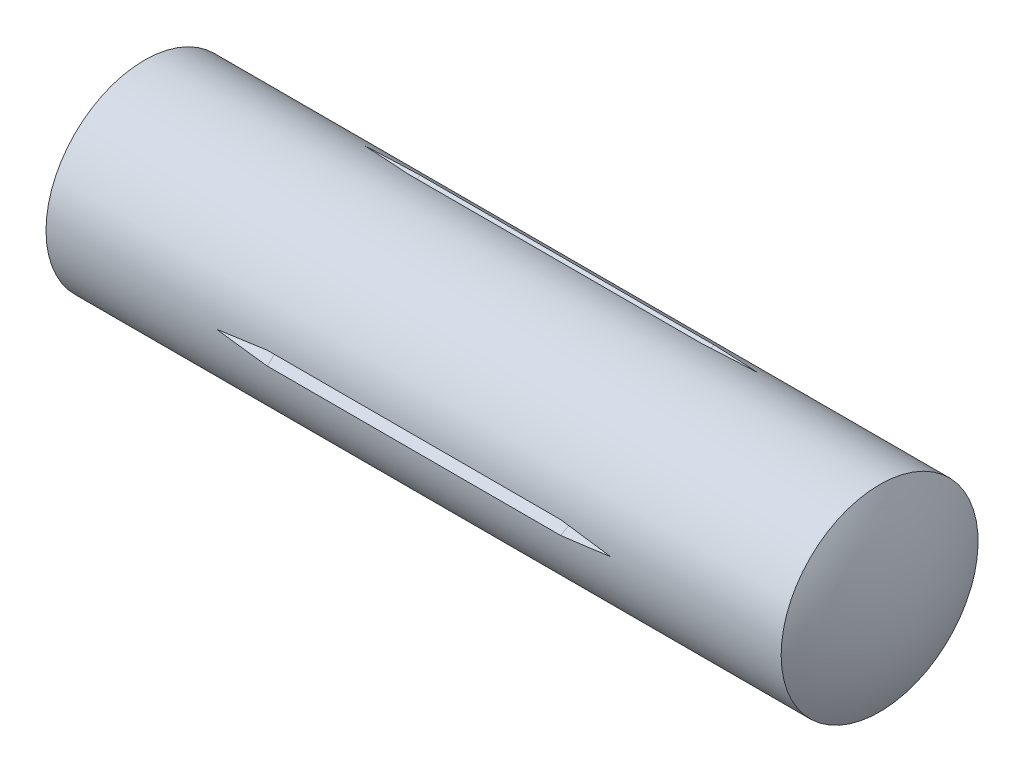
SolidWorks part; units mm, degrees
ref_plane "Plane1" through (0, 0, 0) normal (0, 0, 1) x (1, 0, 0)
ref_plane "Plane2" through (0, 0, 0) normal (0, 1, 0) x (1, 0, 0)
ref_plane "Plane3" through (0, 0, 0) normal (1, 0, 0) x (0, 0, -1)
sketch "Sketch1" plane through (0, 0, 0) normal (0, 0, 1) x (1, 0, 0)
  line L0 (-57, 0) -> (60, 0) construction
  line L1 (-50, 0) -> (-50, 1.25)
  line L2 (-46.6819, 12.5) -> (46.6506, 12.5)
  line L3 (-50, 0) -> (50, 0)
  arc A0 (-46.6819, 12.5) -> (-50, 1.25) centre (-25.0313, 0) ccw
  arc A1 (50, 0) -> (46.6506, 12.5) centre (25, 0) ccw
  dimension "D1" = 25
  dimension "D2" = 25
  dimension "Diameter" = 25
  dimension "Length" = 100
  dimension "D3" = 2.5
revolve "Base-Revolve" add sketch "Sketch1" angle 360 about L0
sketch "Sketch3" plane through (0, 0, 0) normal (0, 1, 0) x (1, 0, 0)
  line L0 (0, 0) -> (60, 0) construction
  line L1 (-57, 0) -> (60, 0) construction
  line L2 (-25, -12.5) -> (-18.75, -11.25)
  line L3 (-18.75, -11.25) -> (18.75, -11.25)
  line L4 (18.75, -11.25) -> (25, -12.5)
  dimension "D1" = 25
  dimension "D2" = 50
  dimension "D3" = 25
  dimension "D4" = 22.5
  dimension "D5" = 6.25
  dimension "D6" = 6.25
ref_plane "Plane4" through (-25, 0, 0) normal (1, 0, 0) x (0, 0, -1)
sketch "Sketch4" plane through (-25, 0, 0) normal (1, 0, 0) x (0, 0, -1)
  line L0 (0, 0) -> (-14, 0) construction
  line L1 (-12.5, 0) -> (-14.3784, 1.3152)
  line L2 (-12.5, 0) -> (-14.3784, -1.3152)
  line L3 (-14.3784, -1.3152) -> (-14.3784, 1.3152)
  circle A0 centre (0, 0) radius 12.5 construction
  dimension "D1" = 25
  dimension "D2" = 70
  dimension "D3" = 35
  dimension "D4" = 1.8784
sweep "Cut-Sweep3" cut profiles "Sketch4" path "Sketch3"
pattern_circular "CirPattern2" count 3 over 360 about axis through (0, 0, 0) along (1, 0, 0) of "Cut-Sweep3"
equation "\"D1@Sketch1\" = \"Diameter@Sketch1\""
equation "\"D2@Sketch1\" = \"Diameter@Sketch1\""
equation "\"D3@Sketch1\" = \"Diameter@Sketch1\" * .1"
equation "\"D1@Sketch3\" = \"Diameter@Sketch1\""
equation "\"D2@Sketch3\" = \"Length@Sketch1\" / 2"
equation "\"D3@Sketch3\" = \"D2@Sketch3\" / 2"
equation "\"D4@Sketch3\" = \"Diameter@Sketch1\" * .9"
equation "\"D5@Sketch3\" = \"D1@Sketch1\" / 4"
equation "\"D6@Sketch3\" = \"D5@Sketch3\""
equation "\"D1@Plane4\" = \"D3@Sketch3\""
equation "\"D1@Sketch4\" = \"Diameter@Sketch1\""
equation "\"D3@Sketch4\" = \"D2@Sketch4\" / 2"
